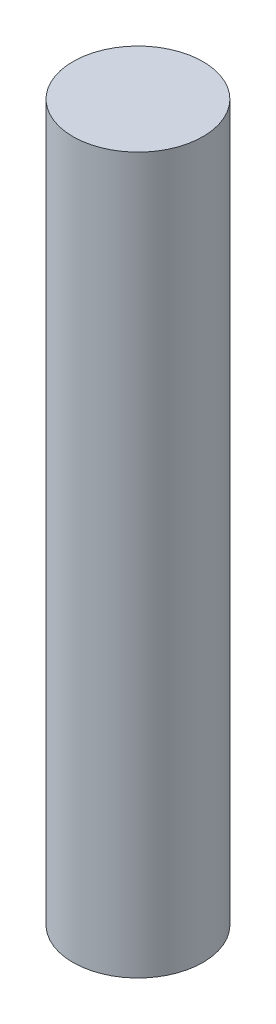
SolidWorks part; units mm, degrees
ref_plane "Front Plane" through (0, 0, 0) normal (0, 0, 1) x (1, 0, 0)
ref_plane "Top Plane" through (0, 0, 0) normal (0, 1, 0) x (1, 0, 0)
ref_plane "Right Plane" through (0, 0, 0) normal (1, 0, 0) x (0, 0, -1)
sketch "Sketch1" plane through (0, 0, 0) normal (0, 1, 0) x (1, 0, 0)
  circle A0 centre (0, 0) radius 1.524
  dimension "D1" = 3.048
extrude "Boss-Extrude1" add sketch "Sketch1" along normal blind 16.764
